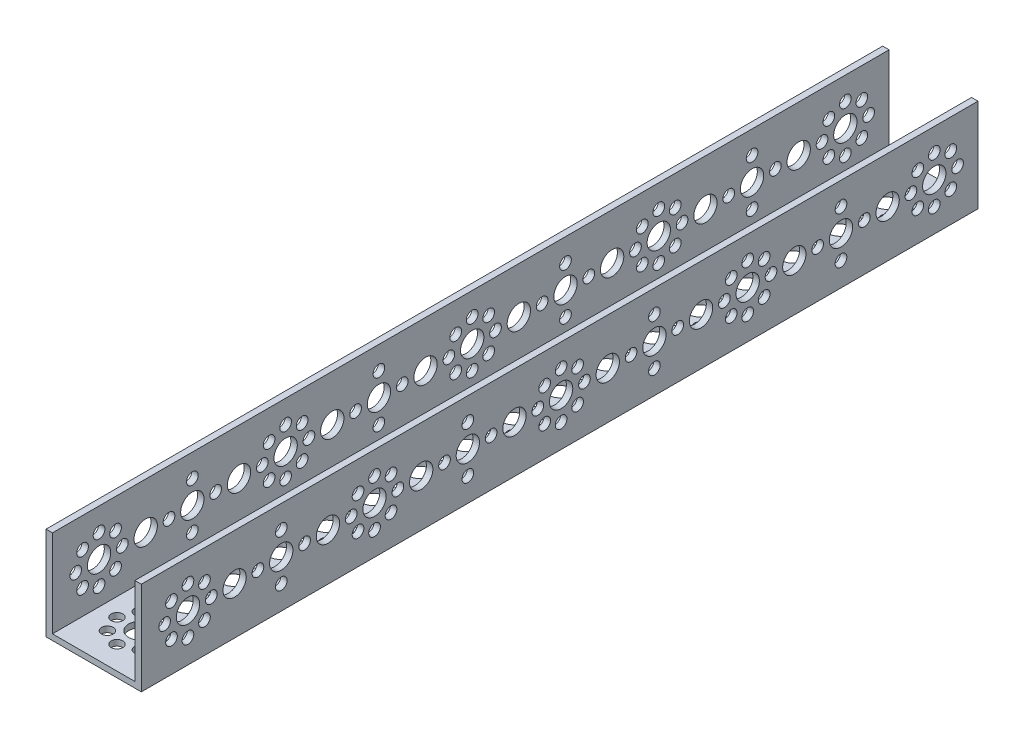
SolidWorks part; units mm, degrees
ref_plane "Front Plane" through (0, 0, 0) normal (0, 0, 1) x (1, 0, 0)
ref_plane "Top Plane" through (0, 0, 0) normal (0, 1, 0) x (1, 0, 0)
ref_plane "Right Plane" through (0, 0, 0) normal (1, 0, 0) x (0, 0, -1)
sketch "Esquisse1" plane through (0, 0, 0) normal (0, 0, 1) x (1, 0, 0)
  line L0 (0, 0) -> (0, 32)
  line L1 (0, 32) -> (2.2, 32)
  line L2 (2.2, 32) -> (2.2, 2)
  line L3 (2.2, 2) -> (30.5, 2)
  line L4 (30.5, 2) -> (30.5, 32)
  line L5 (30.5, 32) -> (32.7, 32)
  line L6 (32.7, 32) -> (32.7, 0)
  line L7 (32.7, 0) -> (0, 0)
  dimension "D1" = 32
  dimension "D2" = 2.2
  dimension "D3" = 2.2
  dimension "D4" = 2
  dimension "D5" = 32
  dimension "D6" = 32.7
  dimension "D7" = 28.3
extrude "Boss.-Extru.1" add sketch "Esquisse1" along normal blind 287
ref_plane "Plan1" through (0, 0, 0) normal (0, -1, 0) x (-1, 0, 0)
sketch "Esquisse2" plane through (0, 0, 0) normal (0, -1, 0) x (-1, 0, 0)
  line L0 (0, -287) -> (-32.7, -287) construction
  line L1 (-32.7, -287) -> (-32.7, 0) construction
  circle A0 centre (-16.35, -271) radius 4
  point P4 (-16.35, -287)
  dimension "D1" = 8
  dimension "D2" = 16
  dimension "D3" = 16.35
extrude "Enlèv. mat.-Extru.1" cut sketch "Esquisse2" against normal through all both and the other way through all
pattern_linear "Répétition linéaire1" count 17 spacing 16 along (0, 0, -1) of "Enlèv. mat.-Extru.1"
sketch "Esquisse3" plane through (0, 0, 0) normal (0, -1, 0) x (1, 0, 0)
  circle A0 centre (24.35, 271) radius 2
  circle A1 centre (16.35, 271) radius 4 construction
  dimension "D1" = 4
  dimension "D2" = 8
  dimension "D3" = 0
extrude "Enlèv. mat.-Extru.2" cut sketch "Esquisse3" against normal through all both and the other way through all contours A0
pattern_circular "Répétition circulaire1" count 4 over 360 about axis through (16.35, 0, 271) along (0, 1, 0) of "Enlèv. mat.-Extru.2"
pattern_circular "Répétition circulaire2" count 8 over 360 about axis through (16.35, 0, 271) along (0, 1, 0) skipping 2, 4, 6 of "Enlèv. mat.-Extru.2"
pattern_linear "Répétition linéaire2" count 17 spacing 16 along (0, 0, -1) skipping (1, 0), (3, 0), (5, 0), (7, 0), (9, 0), (11, 0), (13, 0), (15, 0) of "Répétition circulaire1", "Enlèv. mat.-Extru.2"
pattern_linear "Répétition linéaire3" count 17 spacing 16 along (0, 0, -1) skipping (1, 0), (2, 0), (3, 0), (5, 0), (6, 0), (7, 0), (9, 0), (10, 0), (11, 0), (13, 0), (14, 0), (15, 0) of "Répétition circulaire2"
ref_plane "Plan4" through (30.5, 0, 0) normal (-1, 0, 0) x (0, 0, 1)
ref_point "Point2" parameters "D1"=28.3
ref_plane "Plan5" through (0.1, -0.1, 0) normal (0.7071, -0.7071, 0) x (0, 0, -1)
mirror "Symétrie2" about plane through (0.1, -0.1, 0) normal (0.7071, -0.7071, 0) of "Répétition linéaire3", "Répétition linéaire2", "Répétition circulaire2", "Répétition circulaire1", "Enlèv. mat.-Extru.2", "Répétition linéaire1", "Enlèv. mat.-Extru.1"
